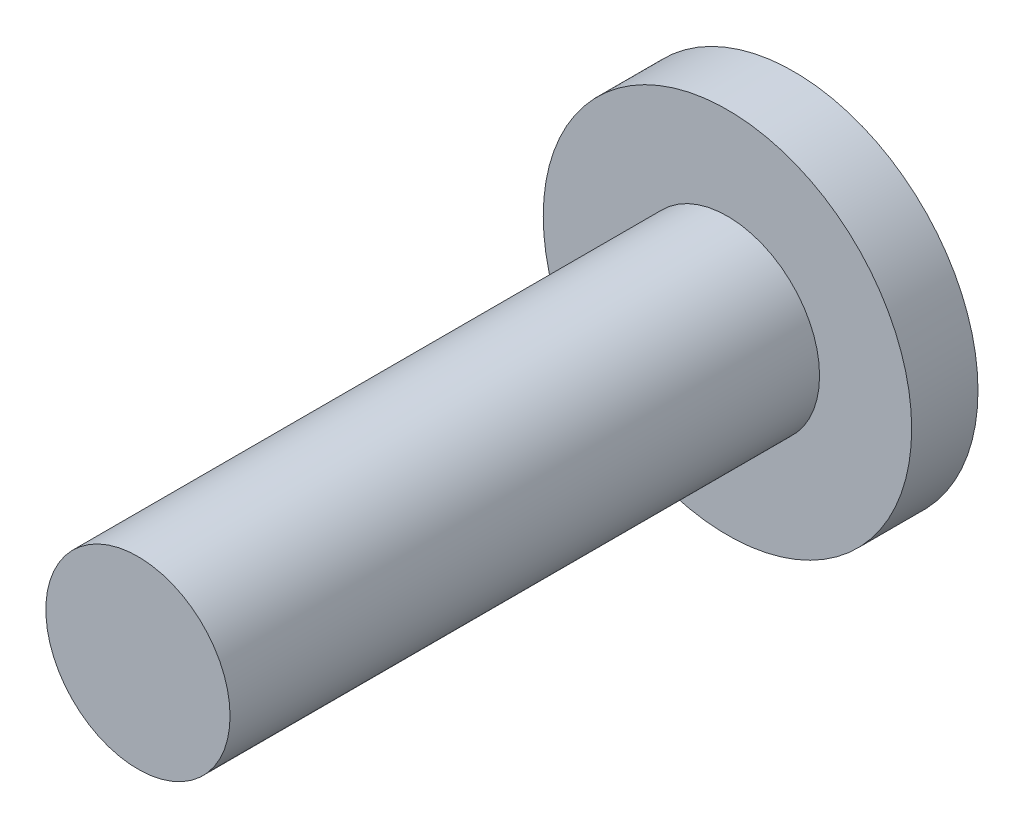
SolidWorks part; units mm, degrees
material "AISI 304"
ref_plane "前视基准面" through (0, 0, 0) normal (0, 0, 1) x (1, 0, 0)
ref_plane "上视基准面" through (0, 0, 0) normal (0, 1, 0) x (1, 0, 0)
ref_plane "右视基准面" through (0, 0, 0) normal (1, 0, 0) x (0, 0, -1)
other "Configuration Table"
sketch "草图1" plane through (0, 0, 0) normal (0, 0, 1) x (1, 0, 0)
  circle A0 centre (0, 0) radius 2.5
  dimension "D1" = 5
extrude "凸台-拉伸1" add sketch "草图1" along normal blind 0.9
sketch "草图2" plane through (0, 0, 0.9) normal (0, 0, 1) x (1, 0, 0)
  circle A0 centre (0, 0) radius 1.25
  dimension "D1" = 2.5
extrude "凸台-拉伸2" add sketch "草图2" along normal blind 8
sketch "草图3" plane through (0, 0, 0) normal (0, 0, -1) x (-1, 0, 0)
  line L1 (0.866, 0) -> (0.433, 0.75)
  line L2 (0.433, 0.75) -> (-0.433, 0.75)
  line L3 (-0.433, 0.75) -> (-0.866, 0)
  line L4 (-0.866, 0) -> (-0.433, -0.75)
  line L5 (-0.433, -0.75) -> (0.433, -0.75)
  line L6 (0.433, -0.75) -> (0.866, 0)
  circle A0 centre (0, 0) radius 0.75 construction
  dimension "D1" = 1.5
extrude "切除-拉伸1" cut sketch "草图3" against normal blind 1
